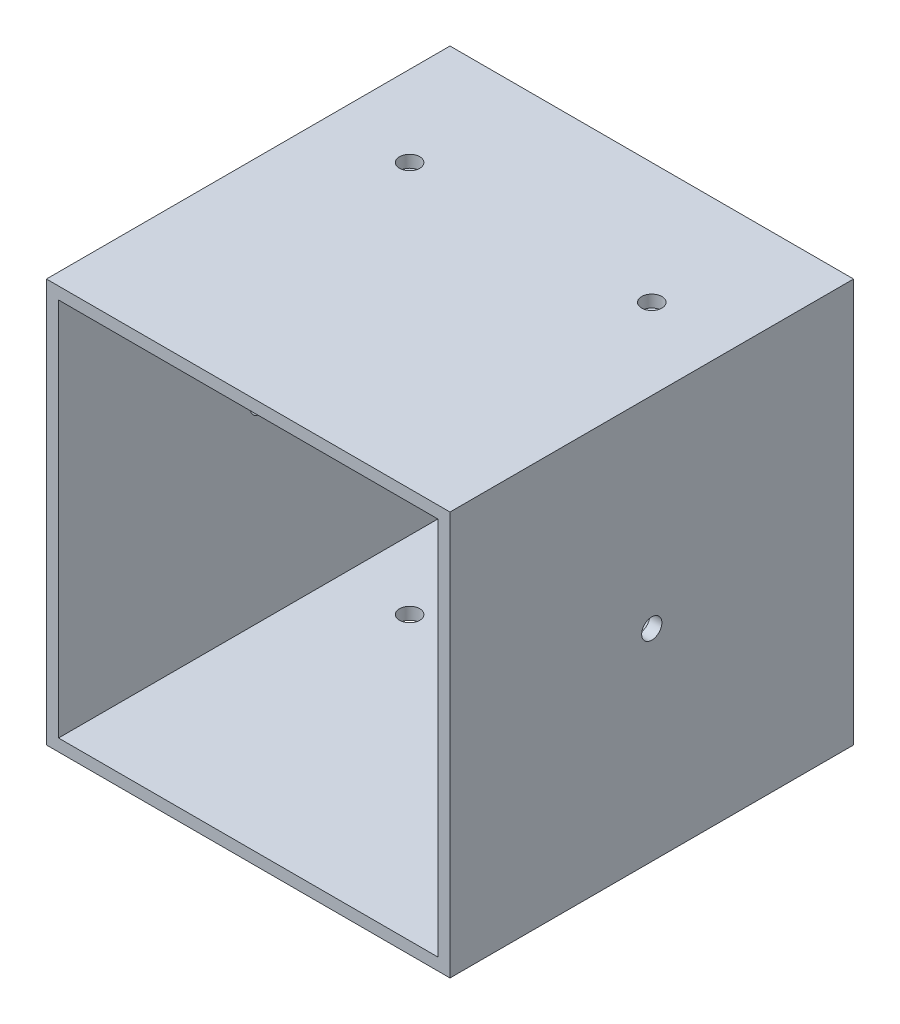
SolidWorks part; units mm, degrees
ref_plane "前基準面" through (0, 0, 0) normal (0, 0, 1) x (1, 0, 0)
ref_plane "上基準面" through (0, 0, 0) normal (0, 1, 0) x (1, 0, 0)
ref_plane "右基準面" through (0, 0, 0) normal (1, 0, 0) x (0, 0, -1)
sketch "草圖1" plane through (0, 0, 0) normal (0, 0, 1) x (1, 0, 0)
  line L0 (-47, 47) -> (47, 47)
  line L1 (-50, -50) -> (50, -50)
  line L2 (-50, -50) -> (-50, 50)
  line L3 (-50, 50) -> (50, 50)
  line L4 (50, -50) -> (50, 50)
  line L5 (-50, -50) -> (50, 50) construction
  line L6 (-50, 50) -> (50, -50) construction
  line L7 (47, -47) -> (47, 47)
  line L8 (-47, -47) -> (47, -47)
  line L9 (-47, -47) -> (-47, 47)
  point P0 (0, 0)
  dimension "D1" = 100
  dimension "D2" = 100
  dimension "D3" = 3
extrude "填料-伸長1" add sketch "草圖1" along normal mid plane 100
sketch "草圖4" plane through (-47, 0, 0) normal (1, 0, 0) x (0, 0, -1)
  line L0 (0, 0) -> (0, 40) construction
  line L1 (-33, 40) -> (33, 40)
  line L3 (-33, 40) -> (-33, 37)
  line L4 (-33, 37) -> (33, 37)
  line L5 (33, 37) -> (33, 40)
  point P8 (0, 40)
  dimension "D1" = 40
  dimension "D2" = 66
  dimension "D3" = 3
extrude "填料-伸長2" add sketch "草圖4" along normal up to next
sketch "草圖2" plane through (0, 0, 0) normal (1, 0, 0) x (0, 0, -1)
  circle A0 centre (0, 0) radius 2.5
  dimension "D1" = 5
extrude "除料-伸長1" cut sketch "草圖2" against normal mid plane 100
sketch "草圖9" plane through (0, 50, 0) normal (0, 1, 0) x (1, 0, 0)
  circle A2 centre (-30, 20) radius 2.5
  circle A3 centre (30, 20) radius 2.5
  circle A4 centre (-30, 0) radius 2.5 construction
  circle A5 centre (30, 0) radius 2.5 construction
  dimension "D2" = 30
  dimension "D5" = 5
  dimension "D6" = 5
  dimension "D9" = 5
  dimension "D10" = 5
  dimension "D3" = 30
  dimension "D4" = 20
  dimension "D7" = 20
extrude "除料-伸長5" cut sketch "草圖9" against normal through all
sketch "草圖10" plane through (0, 40, 0) normal (0, 1, 0) x (1, 0, 0)
  circle A0 centre (-30, 0) radius 2.5
  circle A1 centre (30, 0) radius 2.5
  dimension "D1" = 5
  dimension "D2" = 5
extrude "除料-伸長6" cut sketch "草圖10" against normal blind 20
